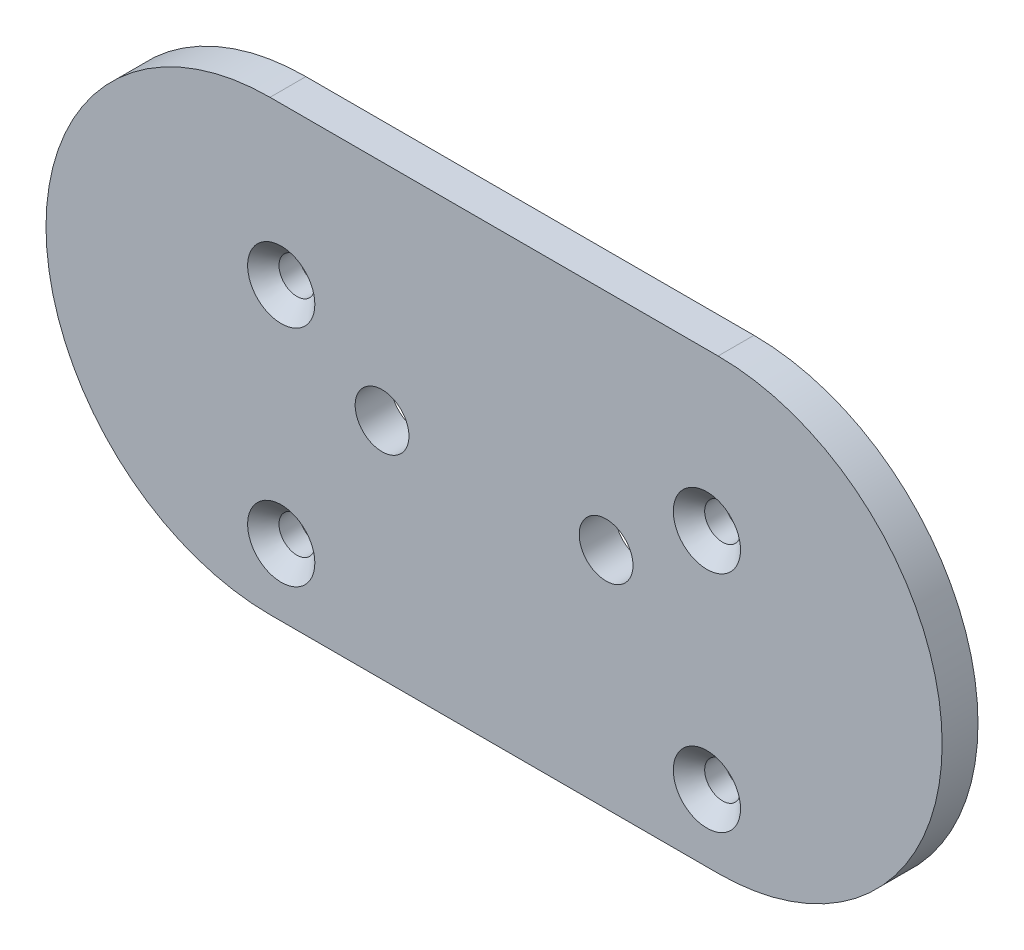
SolidWorks part; units mm, degrees
ref_plane "前视基准面" through (0, 0, 0) normal (0, 0, 1) x (1, 0, 0)
ref_plane "上视基准面" through (0, 0, 0) normal (0, 1, 0) x (1, 0, 0)
ref_plane "右视基准面" through (0, 0, 0) normal (1, 0, 0) x (0, 0, -1)
sketch "草图1" plane through (0, 0, 0) normal (0, 0, 1) x (1, 0, 0)
  line L0 (-20, 0) -> (20, 0) construction
  line L5 (-20, 20) -> (20, 20)
  line L6 (-20, -20) -> (20, -20)
  arc A0 (-20, 20) -> (-20, -20) centre (-20, 0) ccw
  arc A1 (20, -20) -> (20, 20) centre (20, 0) ccw
  circle A2 centre (-19, -14) radius 1.6
  circle A3 centre (19, -14) radius 1.6
  circle A4 centre (19, 6) radius 1.6
  circle A5 centre (-19, 6) radius 1.6
  circle A6 centre (-10, 0) radius 2.4
  circle A7 centre (10, 0) radius 2.4
  point P2 (0, 0)
  point P21 (0, 0)
  dimension "D1" = 20
  dimension "D5" = 19
  dimension "D7" = 3.2
  dimension "D8" = 4.8
  dimension "D9" = 20
  dimension "D2" = 40
  dimension "D6" = 6
  dimension "D10" = 10
  dimension "D3" = 2
  dimension "D4" = 2
extrude "凸台-拉伸1" add sketch "草图1" along normal blind 3.2
chamfer "倒角1" distance 1.4 angle 45 4 edges at (20.6, -14, 3.2) (20.6, 6, 3.2) (-17.4, -14, 3.2) (-17.4, 6, 3.2)
